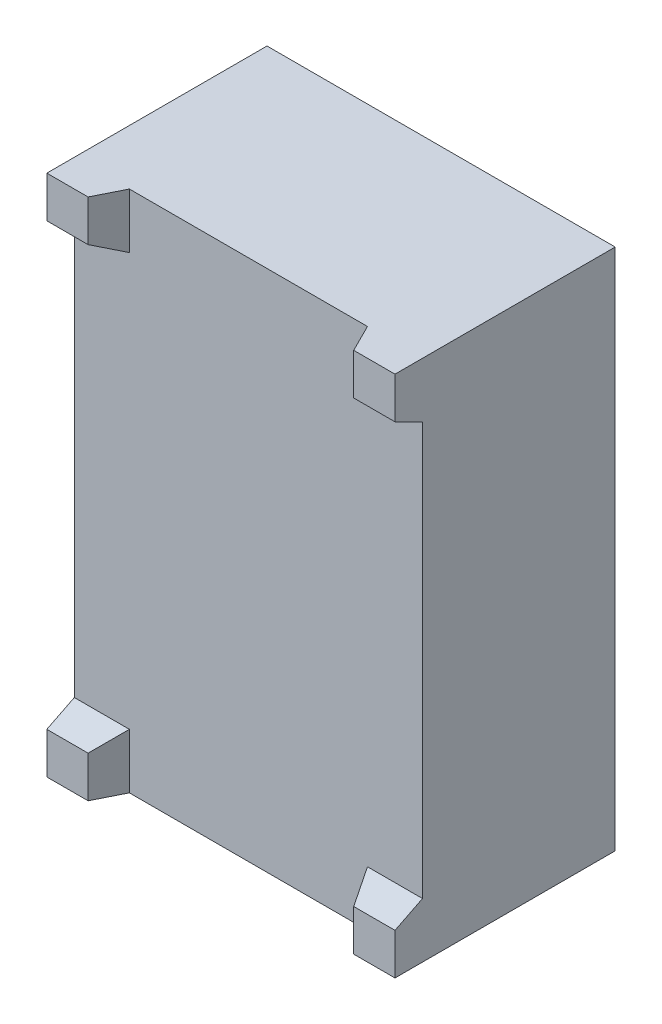
SolidWorks part; units mm, degrees
ref_plane "Ön Düzlem" through (0, 0, 0) normal (0, 0, 1) x (1, 0, 0)
ref_plane "Üst Düzlem" through (0, 0, 0) normal (0, 1, 0) x (1, 0, 0)
ref_plane "Sağ Düzlem" through (0, 0, 0) normal (1, 0, 0) x (0, 0, -1)
sketch "Çizim1" plane through (0, 0, 0) normal (0, 0, 1) x (1, 0, 0)
  line L1 (-6.325, -9.5) -> (6.325, -9.5)
  line L2 (-6.325, -9.5) -> (-6.325, 9.5)
  line L3 (-6.325, 9.5) -> (6.325, 9.5)
  line L4 (6.325, -9.5) -> (6.325, 9.5)
  line L5 (-6.325, -9.5) -> (6.325, 9.5) construction
  line L6 (-6.325, 9.5) -> (6.325, -9.5) construction
  point P0 (0, 0)
  dimension "D1" = 12.65
  dimension "D2" = 19
extrude "Yükseklik-Ekstrüzyon1" add sketch "Çizim1" along normal blind 7.75
sketch "Çizim2" plane through (0, 9.5, 0) normal (0, 1, 0) x (1, 0, 0)
  line L0 (-4.825, -7.75) -> (-4.325, -6.75)
  line L1 (6.325, -7.75) -> (-6.325, -7.75) construction
  line L2 (4.825, -7.75) -> (4.325, -6.75)
  line L3 (6.325, -7.75) -> (6.325, 0) construction
  line L5 (-6.325, -7.75) -> (-6.325, 0) construction
  line L6 (4.325, -6.75) -> (-4.325, -6.75)
  dimension "D1" = 1
  dimension "D2" = 1.5
  dimension "D3" = 2
  dimension "D4" = 2
  dimension "D5" = 1
  dimension "D6" = 1.5
extrude "Kes-Ekstrüzyon1" cut sketch "Çizim2" against normal through all
sketch "Çizim3" plane through (-6.325, 0, 0) normal (-1, 0, 0) x (0, 0, 1)
  line L0 (7.75, 8) -> (6.75, 7.5)
  line L1 (7.75, 9.5) -> (7.75, -9.5) construction
  line L2 (6.75, 7.5) -> (6.75, -7.5)
  line L3 (6.75, -7.5) -> (7.75, -8)
  line L4 (7.75, 9.5) -> (0, 9.5) construction
  line L5 (7.75, -9.5) -> (0, -9.5) construction
  line L6 (7.75, 8) -> (7.75, -8)
  dimension "D1" = 1
  dimension "D2" = 1.5
  dimension "D3" = 2
  dimension "D4" = 1.5
  dimension "D5" = 2
extrude "Kes-Ekstrüzyon2" cut sketch "Çizim3" against normal through all
sketch "Çizim4" plane through (0, 0, 0) normal (0, 0, -1) x (-1, 0, 0)
  line L0 (6.175, 6.8586) -> (5.175, 6.8586) construction
  line L1 (-6.175, -9.3414) -> (6.175, -9.3414)
  line L2 (-6.175, -9.3414) -> (-6.175, 9.3586)
  line L3 (-6.175, 9.3586) -> (6.175, 9.3586)
  line L4 (6.175, -9.3414) -> (6.175, 9.3586)
  line L5 (-6.175, -6.8414) -> (-5.175, -6.8414) construction
  line L6 (6.175, -6.8414) -> (3.175, -6.8414) construction
  line L7 (-6.175, 6.8586) -> (-3.175, 6.8586) construction
  line L8 (5.0079, 5.7142) -> (4.2467, 0.5)
  line L9 (4.0184, 6.8586) -> (3.675, 6.8586)
  line L10 (3.675, 6.8586) -> (2.8783, 1.4016)
  line L11 (1.675, -6.8414) -> (2.3104, -6.8414)
  line L12 (-17.0946, 0) -> (17.0946, 0) construction
  line L13 (2.8783, 1.4016) -> (3.7467, 0.5)
  line L14 (3.7467, 0.5) -> (4.2467, 0.5)
  line L15 (3.6007, -0.5) -> (4.1007, -0.5)
  line L16 (3.6007, -0.5) -> (2.4913, -1.25)
  line L17 (2.4913, -1.25) -> (1.675, -6.8414)
  line L18 (4.1007, -0.5) -> (3.2999, -5.9858)
  line L19 (-3.2999, 6.0031) -> (-4.1033, 0.5)
  line L20 (-4.1033, 0.5) -> (-3.6033, 0.5)
  line L21 (-3.6033, 0.5) -> (-2.5066, 1.1619)
  line L22 (-2.5066, 1.1619) -> (-1.675, 6.8586)
  line L23 (-1.675, 6.8586) -> (-2.3104, 6.8586)
  line L24 (-5.0079, -5.6969) -> (-4.2493, -0.5)
  line L25 (-4.2493, -0.5) -> (-3.7493, -0.5)
  line L26 (-3.7493, -0.5) -> (-2.8587, -1.25)
  line L27 (-2.8587, -1.25) -> (-3.675, -6.8414)
  line L28 (-3.675, -6.8414) -> (-4.0184, -6.8414)
  line L29 (-3.072, -5.3414) -> (-3.291, -6.8414)
  line L30 (-2.5066, 0.75) -> (2.8783, 0.75)
  line L31 (-2.5066, 0.75) -> (-3.7493, 0)
  line L32 (-3.072, -5.3414) -> (1.51, -5.3414)
  line L33 (-2.8587, -0.75) -> (2.4913, -0.75)
  line L34 (-3.7493, 0) -> (-2.8587, -0.75)
  line L35 (2.8783, 0.75) -> (3.6007, 0)
  line L36 (3.6007, 0) -> (2.4913, -0.75)
  line L37 (1.51, -5.3414) -> (1.291, -6.8414)
  line L38 (-3.291, -6.8414) -> (1.291, -6.8414)
  line L39 (-1.291, 6.8586) -> (-1.51, 5.3586)
  line L40 (-1.291, 6.8586) -> (3.291, 6.8586)
  line L42 (-1.51, 5.3586) -> (3.072, 5.3586)
  line L43 (-6.325, -9.5) -> (-6.325, 9.5) construction
  line L44 (3.291, 6.8586) -> (3.072, 5.3586)
  arc A0 (5.0079, 5.7142) -> (4.0184, 6.8586) centre (4.0184, 5.8586) ccw
  arc A1 (2.3104, -6.8414) -> (3.2999, -5.9858) centre (2.3104, -5.8414) ccw
  arc A2 (-2.3104, 6.8586) -> (-3.2999, 6.0031) centre (-2.3104, 5.8586) ccw
  arc A3 (-5.0079, -5.6969) -> (-4.0184, -6.8414) centre (-4.0184, -5.8414) ccw
  circle A4 centre (4.975, -6.0914) radius 0.75
  point P0 (0, 0)
  point P20 (0, 0)
  point P21 (0, 0)
  dimension "D12" = 1
  dimension "D17" = 1
  dimension "D22" = 1
  dimension "D27" = 1
  dimension "D32" = 1.5
  dimension "D33" = 1.2
  dimension "D1" = 1
  dimension "D2" = 12.35
  dimension "D3" = 18.7
  dimension "D4" = 1
  dimension "D5" = 2.5
  dimension "D6" = 2.5
  dimension "D7" = 3
  dimension "D8" = 3
  dimension "D9" = 1.5
  dimension "D10" = 0.5
  dimension "D11" = 1.5
  dimension "D13" = 0.5
  dimension "D14" = 0.5
  dimension "D15" = 0.38
  dimension "D16" = 0.5
  dimension "D18" = 0.5
  dimension "D19" = 1.5
  dimension "D20" = 0.38
  dimension "D21" = 0.5
  dimension "D23" = 1.5
  dimension "D24" = 0.5
  dimension "D25" = 0.5
  dimension "D26" = 0.38
  dimension "D28" = 0.75
  dimension "D29" = 0.75
  dimension "D30" = 0.38
  dimension "D31" = 1.5
  dimension "D34" = 0.15
extrude "Yükseklik-Ekstrüzyon2" add sketch "Çizim4" along normal blind 0.25 separate body
sketch "Çizim5" plane through (0, 0, -0.25) normal (0, 0, -1) x (-1, 0, 0)
  line L0 (3.291, 6.8586) -> (-1.291, 6.8586) construction
  line L1 (3.072, 5.3586) -> (3.291, 6.8586) construction
  line L2 (-1.51, 5.3586) -> (3.072, 5.3586) construction
  line L3 (-1.291, 6.8586) -> (-1.51, 5.3586) construction
  line L4 (-2.5066, 1.1619) -> (-1.675, 6.8586) construction
  line L5 (-1.675, 6.8586) -> (-2.3104, 6.8586) construction
  line L6 (-3.2999, 6.0031) -> (-4.1033, 0.5) construction
  line L7 (-3.6033, 0.5) -> (-2.5066, 1.1619) construction
  line L8 (-4.1033, 0.5) -> (-3.6033, 0.5) construction
  line L9 (-2.5066, 0.75) -> (-3.7493, 0) construction
  line L10 (2.8783, 0.75) -> (-2.5066, 0.75) construction
  line L11 (3.6007, 0) -> (2.8783, 0.75) construction
  line L12 (2.4913, -0.75) -> (3.6007, 0) construction
  line L13 (-2.8587, -0.75) -> (2.4913, -0.75) construction
  line L14 (-3.7493, 0) -> (-2.8587, -0.75) construction
  line L15 (-2.8587, -1.25) -> (-3.7493, -0.5) construction
  line L16 (-3.7493, -0.5) -> (-4.2493, -0.5) construction
  line L17 (-4.2493, -0.5) -> (-5.0079, -5.6969) construction
  line L18 (-3.675, -6.8414) -> (-2.8587, -1.25) construction
  line L19 (3.675, 6.8586) -> (2.8783, 1.4016) construction
  line L20 (4.0184, 6.8586) -> (3.675, 6.8586) construction
  line L21 (4.2467, 0.5) -> (5.0079, 5.7142) construction
  line L22 (3.7467, 0.5) -> (4.2467, 0.5) construction
  line L23 (2.8783, 1.4016) -> (3.7467, 0.5) construction
  line L24 (3.6007, -0.5) -> (2.4913, -1.25) construction
  line L25 (4.1007, -0.5) -> (3.6007, -0.5) construction
  line L26 (3.2999, -5.9858) -> (4.1007, -0.5) construction
  line L27 (2.4913, -1.25) -> (1.675, -6.8414) construction
  line L28 (-4.0184, -6.8414) -> (-3.675, -6.8414) construction
  line L29 (-3.072, -5.3414) -> (-3.291, -6.8414) construction
  line L30 (1.51, -5.3414) -> (-3.072, -5.3414) construction
  line L31 (1.291, -6.8414) -> (1.51, -5.3414) construction
  line L32 (-3.291, -6.8414) -> (1.291, -6.8414) construction
  line L33 (1.675, -6.8414) -> (2.3104, -6.8414) construction
  line L34 (3.291, 6.8586) -> (-1.291, 6.8586)
  line L35 (3.072, 5.3586) -> (3.291, 6.8586)
  line L36 (-1.51, 5.3586) -> (3.072, 5.3586)
  line L37 (-1.291, 6.8586) -> (-1.51, 5.3586)
  line L38 (-2.5066, 1.1619) -> (-1.675, 6.8586)
  line L39 (-1.675, 6.8586) -> (-2.3104, 6.8586)
  line L40 (-3.2999, 6.0031) -> (-4.1033, 0.5)
  line L41 (-3.6033, 0.5) -> (-2.5066, 1.1619)
  line L42 (-4.1033, 0.5) -> (-3.6033, 0.5)
  line L43 (-2.5066, 0.75) -> (-3.7493, 0)
  line L44 (2.8783, 0.75) -> (-2.5066, 0.75)
  line L45 (3.6007, 0) -> (2.8783, 0.75)
  line L46 (2.4913, -0.75) -> (3.6007, 0)
  line L47 (-2.8587, -0.75) -> (2.4913, -0.75)
  line L48 (-3.7493, 0) -> (-2.8587, -0.75)
  line L49 (-2.8587, -1.25) -> (-3.7493, -0.5)
  line L50 (-3.7493, -0.5) -> (-4.2493, -0.5)
  line L51 (-4.2493, -0.5) -> (-5.0079, -5.6969)
  line L52 (-3.675, -6.8414) -> (-2.8587, -1.25)
  line L53 (3.675, 6.8586) -> (2.8783, 1.4016)
  line L54 (4.0184, 6.8586) -> (3.675, 6.8586)
  line L55 (4.2467, 0.5) -> (5.0079, 5.7142)
  line L56 (3.7467, 0.5) -> (4.2467, 0.5)
  line L57 (2.8783, 1.4016) -> (3.7467, 0.5)
  line L58 (3.6007, -0.5) -> (2.4913, -1.25)
  line L59 (4.1007, -0.5) -> (3.6007, -0.5)
  line L60 (3.2999, -5.9858) -> (4.1007, -0.5)
  line L61 (2.4913, -1.25) -> (1.675, -6.8414)
  line L62 (-4.0184, -6.8414) -> (-3.675, -6.8414)
  line L63 (-3.072, -5.3414) -> (-3.291, -6.8414)
  line L64 (1.51, -5.3414) -> (-3.072, -5.3414)
  line L65 (1.291, -6.8414) -> (1.51, -5.3414)
  line L66 (-3.291, -6.8414) -> (1.291, -6.8414)
  line L67 (1.675, -6.8414) -> (2.3104, -6.8414)
  arc A0 (-2.3104, 6.8586) -> (-3.2999, 6.0031) centre (-2.3104, 5.8586) ccw construction
  arc A1 (5.0079, 5.7142) -> (4.0184, 6.8586) centre (4.0184, 5.8586) ccw construction
  arc A2 (-5.0079, -5.6969) -> (-4.0184, -6.8414) centre (-4.0184, -5.8414) ccw construction
  arc A3 (2.3104, -6.8414) -> (3.2999, -5.9858) centre (2.3104, -5.8414) ccw construction
  circle A4 centre (4.975, -6.0914) radius 0.75 construction
  arc A5 (-2.3104, 6.8586) -> (-3.2999, 6.0031) centre (-2.3104, 5.8586) ccw
  arc A6 (5.0079, 5.7142) -> (4.0184, 6.8586) centre (4.0184, 5.8586) ccw
  arc A7 (-5.0079, -5.6969) -> (-4.0184, -6.8414) centre (-4.0184, -5.8414) ccw
  arc A8 (2.3104, -6.8414) -> (3.2999, -5.9858) centre (2.3104, -5.8414) ccw
  circle A9 centre (4.975, -6.0914) radius 0.75
extrude "Yükseklik-Ekstrüzyon3" add sketch "Çizim5" against normal up to surface (0.25 mm away) separate body up to face at (0, 0, 0)
sketch "Çizim6" plane through (0, 0, 0) normal (0, 0, -1) x (-1, 0, 0)
  line L4 (-6.325, 9.5) -> (-6.325, -9.5)
  line L5 (-6.325, -9.5) -> (6.325, -9.5)
  line L6 (6.325, -9.5) -> (6.325, 9.5)
  line L7 (6.325, 9.5) -> (-6.325, 9.5)
  line L8 (-6.325, 9.5) -> (-6.325, -9.5)
  line L9 (-6.325, -9.5) -> (6.325, -9.5)
  line L10 (6.325, -9.5) -> (6.325, 9.5)
  line L11 (6.325, 9.5) -> (-6.325, 9.5)
  line L12 (6.175, -9.3414) -> (6.175, 9.3586)
  line L13 (6.175, 9.3586) -> (-6.175, 9.3586)
  line L14 (-6.175, 9.3586) -> (-6.175, -9.3414)
  line L15 (-6.175, -9.3414) -> (6.175, -9.3414)
  line L16 (6.175, -9.3414) -> (6.175, 9.3586)
  line L17 (6.175, 9.3586) -> (-6.175, 9.3586)
  line L18 (-6.175, 9.3586) -> (-6.175, -9.3414)
  line L19 (-6.175, -9.3414) -> (6.175, -9.3414)
  dimension "D1" = 0
  dimension "D2" = 0
extrude "Yükseklik-Ekstrüzyon4" add sketch "Çizim6" along normal through all
